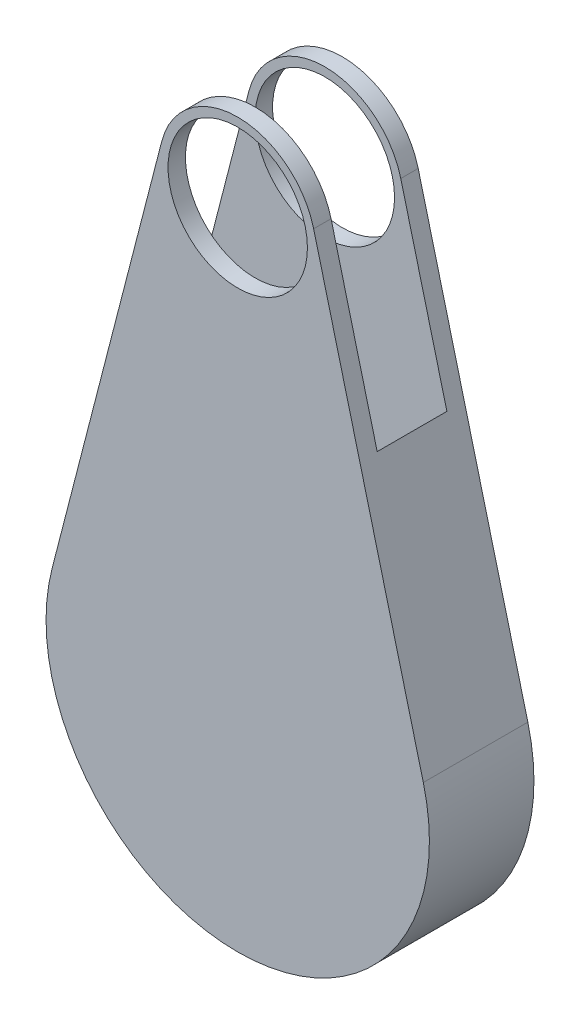
SolidWorks part; units mm, degrees
ref_plane "Front Plane" through (0, 0, 0) normal (0, 0, 1) x (1, 0, 0)
ref_plane "Top Plane" through (0, 0, 0) normal (0, 1, 0) x (1, 0, 0)
ref_plane "Right Plane" through (0, 0, 0) normal (1, 0, 0) x (0, 0, -1)
sketch "Sketch1" plane through (0, 0, 0) normal (0, 0, 1) x (1, 0, 0)
  line L0 (-53.2535, 13.75) -> (-21.7855, 135.625)
  line L1 (21.7855, 135.625) -> (53.2535, 13.75)
  arc A0 (-53.2535, 13.75) -> (53.2535, 13.75) centre (0, 0) ccw
  arc A1 (21.7855, 135.625) -> (-21.7855, 135.625) centre (0, 130) ccw
  dimension "D1" = 110
  dimension "D2" = 45
  dimension "D3" = 130
extrude "Boss-Extrude1" add sketch "Sketch1" along normal mid plane 30
sketch "Sketch2" plane through (0, 0, 15) normal (0, 0, 1) x (1, 0, 0)
  circle A0 centre (0, 130) radius 20
  dimension "D1" = 40
extrude "Cut-Extrude1" cut sketch "Sketch2" against normal blind 45
sketch "Sketch4" plane through (0, 0, 0) normal (0, 0, 1) x (1, 0, 0)
  line L0 (0, 130) -> (0, 53.8368) construction
  line L2 (-21.7855, 135.625) -> (-53.2535, 13.75)
  line L3 (53.2535, 13.75) -> (21.7855, 135.625)
  line L4 (-21.7855, 135.625) -> (-35.0202, 84.3674)
  line L5 (35.0202, 84.3674) -> (21.7855, 135.625)
  arc A1 (-35.0202, 84.3674) -> (35.0202, 84.3674) centre (0, 89.187) ccw
  arc A2 (21.7855, 135.625) -> (-21.7855, 135.625) centre (0, 130) ccw
  arc A3 (-53.2535, 13.75) -> (53.2535, 13.75) centre (0, 0) ccw
  arc A4 (21.7855, 135.625) -> (-21.7855, 135.625) centre (0, 130) ccw
  dimension "D1" = 0
extrude "Cut-Extrude2" cut sketch "Sketch4" against normal mid plane 20
